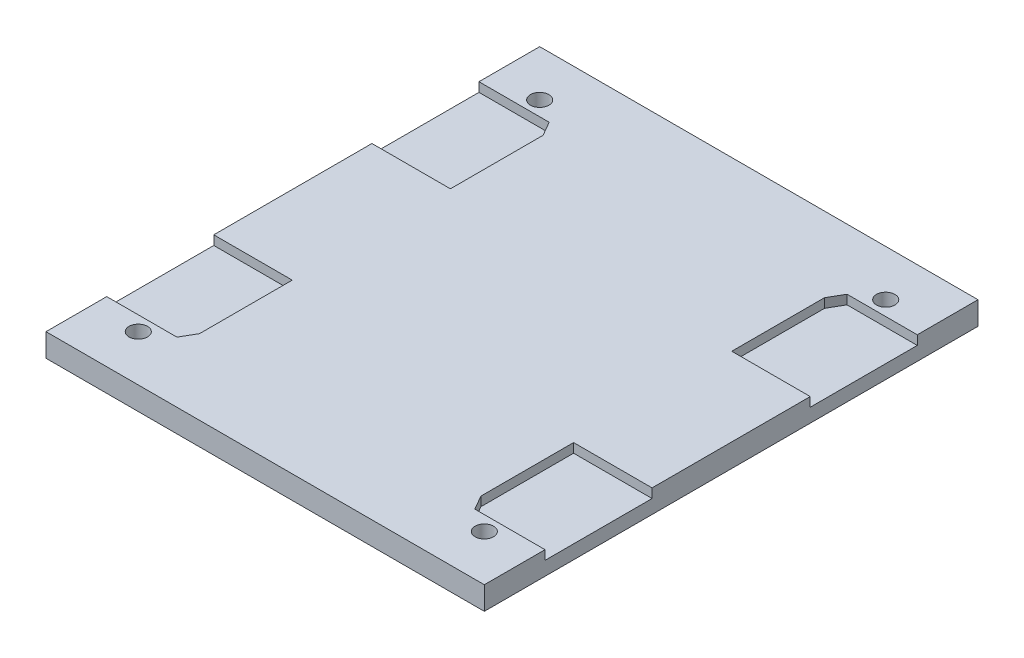
SolidWorks part; units mm, degrees
ref_plane "Front Plane" through (0, 0, 0) normal (0, 0, 1) x (1, 0, 0)
ref_plane "Top Plane" through (0, 0, 0) normal (0, 1, 0) x (1, 0, 0)
ref_plane "Right Plane" through (0, 0, 0) normal (1, 0, 0) x (0, 0, -1)
sketch "Sketch2" plane through (0, 0, 0) normal (0, 1, 0) x (1, 0, 0)
  line L0 (37.5, -43.5) -> (47.5, -43.5)
  line L1 (-47.5, -53.5) -> (47.5, -53.5)
  line L2 (-47.5, -53.5) -> (-47.5, 53.5)
  line L3 (-47.5, 53.5) -> (47.5, 53.5)
  line L4 (47.5, -53.5) -> (47.5, 53.5)
  line L5 (-47.5, -53.5) -> (47.5, 53.5) construction
  line L6 (-47.5, 53.5) -> (47.5, -53.5) construction
  line L7 (37.5, -43.5) -> (37.5, -53.5)
  line L8 (-55, 0) -> (55, 0) construction
  line L9 (0, -55) -> (0, 55) construction
  line L15 (-60, 66) -> (60, 66)
  line L16 (-60, 66) -> (-60, -66)
  line L17 (-60, -66) -> (60, -66)
  line L18 (60, 66) -> (60, -66)
  line L19 (-60, 66) -> (60, -66) construction
  line L20 (-60, -66) -> (60, 66) construction
  circle A1 centre (37.5, -43.5) radius 2
  circle A2 centre (37.5, 43.5) radius 2
  circle A3 centre (-37.5, -43.5) radius 2
  circle A4 centre (-37.5, 43.5) radius 2
  point P0 (0, 0)
  point P20 (0, 0)
  point P21 (0, 0)
  dimension "D3" = 10
  dimension "D5" = 4
  dimension "D1" = 95
  dimension "D2" = 107
  dimension "D4" = 10
  dimension "D6" = 120
  dimension "D7" = 132
extrude "Boss-Extrude1" add sketch "Sketch2" along normal blind 5 contours A1 L0 L4 L3 L2 L1 L7 A4 A2 A3 | A1 L7 L1 L4 L0
sketch "Sketch3" plane through (0, 5, 0) normal (0, 1, 0) x (1, 0, 0)
  line L5 (-47.515, 40.2371) -> (-32.4121, 40.2371) construction
  line L6 (-47.5, -53.5) -> (-47.5, 53.5) construction
  line L10 (-47.5, 17.2402) -> (-47.5, 40.2371)
  line L11 (-47.6, 40.3371) -> (-32.2822, 40.3371)
  line L12 (-32.2822, 40.3371) -> (-30.49, 37.2328)
  line L13 (-30.49, 17.1402) -> (-30.49, 37.2328)
  line L14 (-47.6, 17.1402) -> (-30.49, 17.1402)
  line L15 (-47.6, 17.1402) -> (-47.6, 40.3371)
  line L16 (-47.5, 40.2371) -> (-32.34, 40.2371) construction
  line L17 (-47.5, 17.2402) -> (-30.59, 17.2402) construction
  line L18 (-30.59, 17.2402) -> (-30.59, 37.206) construction
  line L19 (-32.34, 40.2371) -> (-30.59, 37.206) construction
  line L20 (0, 62.7045) -> (0, 59.4045) construction
  line L21 (32.2822, 40.3371) -> (30.49, 37.2328)
  line L22 (30.49, 17.1402) -> (30.49, 37.2328)
  line L23 (47.6, 17.1402) -> (30.49, 17.1402)
  line L24 (47.5, 17.2402) -> (47.5, 40.2371)
  line L25 (47.6, 40.3371) -> (32.2822, 40.3371)
  line L26 (-130.0965, 0) -> (-126.7965, 0) construction
  line L27 (47.5, -17.2402) -> (47.5, -40.2371)
  line L28 (47.6, -17.1402) -> (30.49, -17.1402)
  line L29 (30.49, -17.1402) -> (30.49, -37.2328)
  line L30 (32.2822, -40.3371) -> (30.49, -37.2328)
  line L31 (47.6, -40.3371) -> (32.2822, -40.3371)
  line L32 (-30.49, -17.1402) -> (-30.49, -37.2328)
  line L33 (-32.2822, -40.3371) -> (-30.49, -37.2328)
  line L34 (-47.6, -40.3371) -> (-32.2822, -40.3371)
  line L35 (-47.5, -17.2402) -> (-47.5, -40.2371)
  line L36 (-47.6, -17.1402) -> (-30.49, -17.1402)
  line M16 (47.5, -53.5) -> (47.5, 53.5)
  line M18 (-47.5, 53.5) -> (-47.5, -53.5)
  dimension "D1" = 0.1
extrude "Cut-Extrude1" cut sketch "Sketch3" against normal blind 2 contours L14 L13 L12 L11 M18 | L25 L21 L22 L23 M16 | L31 L28 L29 L30 M16 | L36 L34 L33 L32 M18
